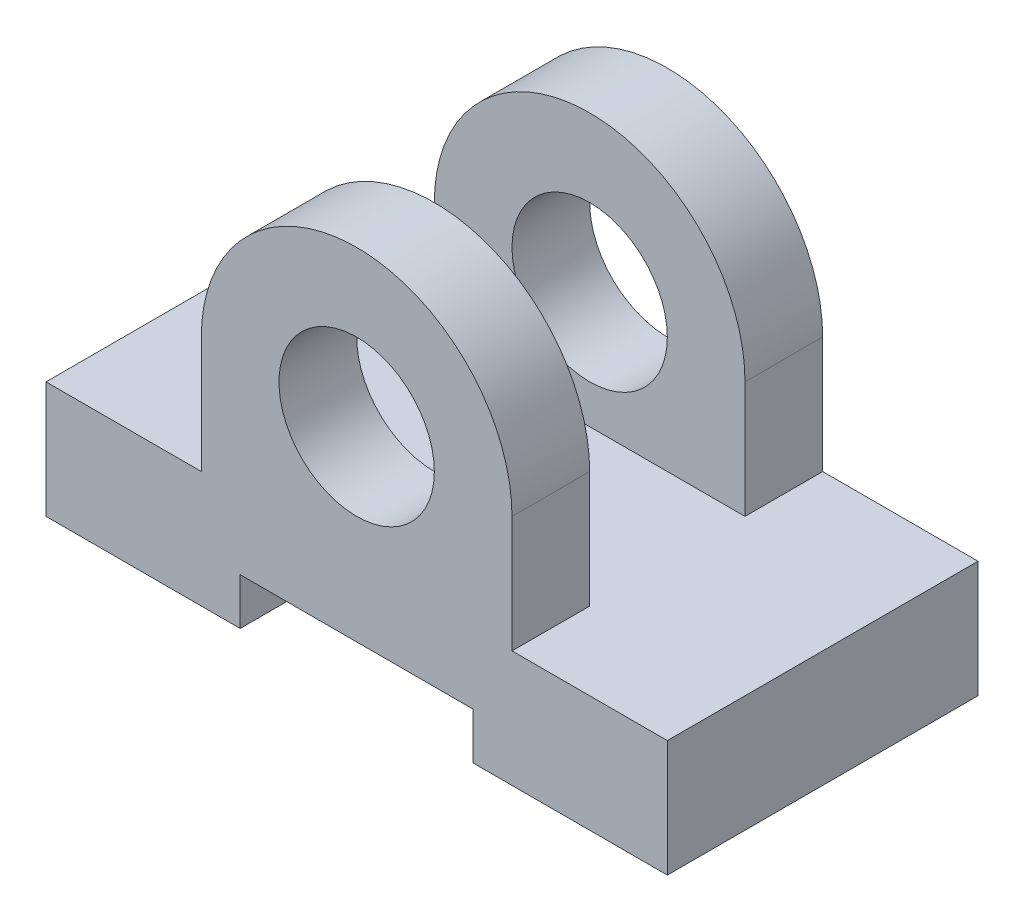
SolidWorks part; units mm, degrees
ref_plane "Plano frontal" through (0, 0, 0) normal (0, 0, 1) x (1, 0, 0)
ref_plane "Plano superior" through (0, 0, 0) normal (0, 1, 0) x (1, 0, 0)
ref_plane "Plano direito" through (0, 0, 0) normal (1, 0, 0) x (0, 0, -1)
sketch "Esboço1" plane through (0, 0, 0) normal (0, 0, 1) x (1, 0, 0)
  line L0 (0, 65.1561) -> (0, -78.0583) construction
  line L1 (-102.1855, 0) -> (142.4404, 0) construction
  line L3 (15, -30) -> (15, -24)
  line L4 (15, -24) -> (-15, -24)
  line L5 (-15, -24) -> (-15, -30)
  line L7 (40, -30) -> (40, -15)
  line L8 (40, -15) -> (20, -15)
  line L9 (20, -15) -> (20, 0)
  line L10 (-40, -30) -> (-40, -15)
  line L11 (-40, -15) -> (-20, -15)
  line L12 (-20, -15) -> (-20, 0)
  line L13 (-40, -30) -> (-15, -30)
  line L14 (15, -30) -> (40, -30)
  arc A0 (-20, 0) -> (20, 0) centre (0, 0) cw
  circle A1 centre (0, 0) radius 10
  point P20 (0, 0)
  point P21 (65.3505, 38.9569)
  point P22 (0, 0)
  dimension "D6" = 20
  dimension "D1" = 15
  dimension "D2" = 80
  dimension "D3" = 30
  dimension "D4" = 6
  dimension "D5" = 30
extrude "Ressalto-extrusão1" add sketch "Esboço1" against normal blind 40
sketch "Esboço2" plane through (-20, 0, 0) normal (-1, 0, 0) x (0, 0, 1)
  line L0 (0, 20) -> (-40, 20) construction
  line L1 (-30, 20) -> (-10, 20)
  line L2 (-30, 20) -> (-30, -15)
  line L3 (-30, -15) -> (-10, -15)
  line L4 (-10, 20) -> (-10, -15)
  line L5 (-40, -15) -> (0, -15) construction
  line L6 (-20, 29.8407) -> (-20, -43.1774) construction
  line L7 (-40, -15) -> (-40, -30) construction
  line L8 (0, -15) -> (0, -30) construction
  dimension "D1" = 20
extrude "Corte-extrusão1" cut sketch "Esboço2" against normal through all both and the other way through all
